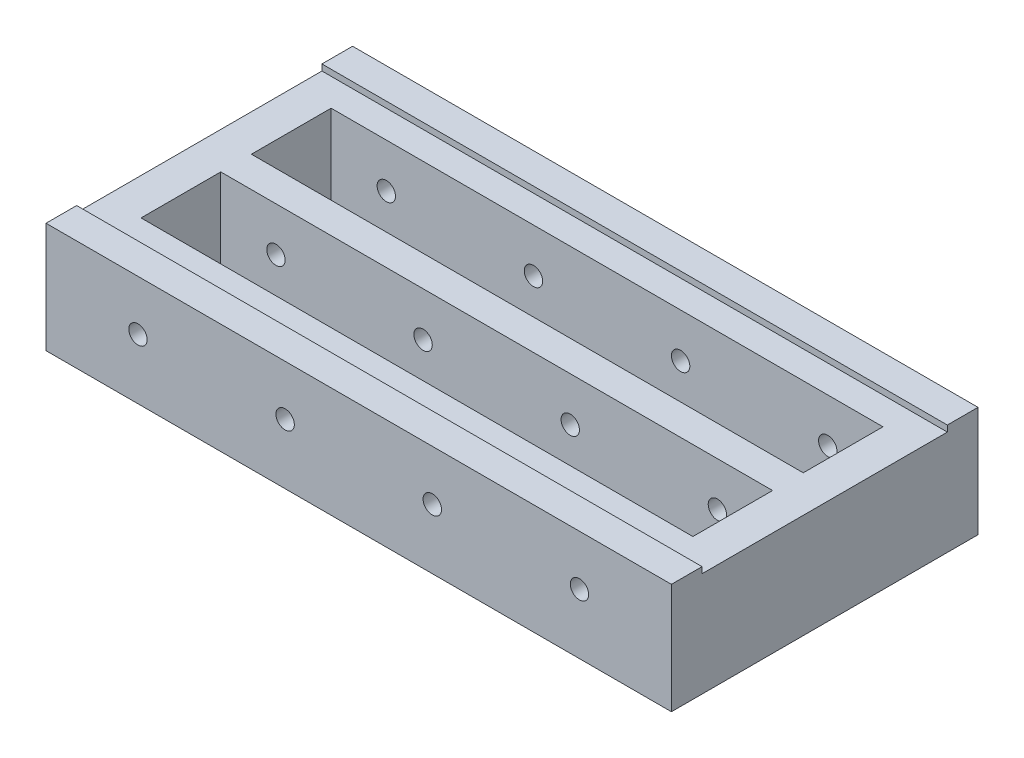
SolidWorks part; units mm, degrees
ref_plane "前视基准面" through (0, 0, 0) normal (0, 0, 1) x (1, 0, 0)
ref_plane "上视基准面" through (0, 0, 0) normal (0, 1, 0) x (1, 0, 0)
ref_plane "右视基准面" through (0, 0, 0) normal (1, 0, 0) x (0, 0, -1)
other "Configuration Table"
sketch "草图1" plane through (0, 0, 0) normal (0, 1, 0) x (1, 0, 0)
  line L0 (-37.5884, 0) -> (30.4411, 0) construction
  line L5 (-25.5, 12.5) -> (25.5, 12.5)
  line L6 (-25.5, 12.5) -> (-25.5, -12.5)
  line L7 (-25.5, -12.5) -> (25.5, -12.5)
  line L8 (25.5, 12.5) -> (25.5, -12.5)
  line L9 (-25.5, 12.5) -> (25.5, -12.5) construction
  line L10 (-25.5, -12.5) -> (25.5, 12.5) construction
  line L11 (-22.5, 7.75) -> (-13.5, 7.75)
  line L12 (-22.5, -1.25) -> (-13.5, -1.25)
  line L13 (-22.5, -1.25) -> (-22.5, -7.75)
  line L14 (-22.5, -7.75) -> (-13.5, -7.75)
  line L15 (-13.5, -1.25) -> (-13.5, -7.75)
  line L20 (-22.5, 7.75) -> (-22.5, 1.25)
  line L21 (-22.5, 1.25) -> (-13.5, 1.25)
  line L22 (-13.5, 7.75) -> (-13.5, 1.25)
  line L23 (-10.5, 7.75) -> (-1.5, 7.75)
  line L24 (-1.5, 7.75) -> (-1.5, 1.25)
  line L25 (-10.5, 1.25) -> (-1.5, 1.25)
  line L26 (-10.5, 7.75) -> (-10.5, 1.25)
  line L27 (-10.5, -1.25) -> (-10.5, -7.75)
  line L28 (-10.5, -1.25) -> (-1.5, -1.25)
  line L29 (-1.5, -1.25) -> (-1.5, -7.75)
  line L30 (-10.5, -7.75) -> (-1.5, -7.75)
  line L31 (1.5, 7.75) -> (10.5, 7.75)
  line L32 (10.5, 7.75) -> (10.5, 1.25)
  line L33 (1.5, 1.25) -> (10.5, 1.25)
  line L34 (1.5, 7.75) -> (1.5, 1.25)
  line L35 (1.5, -1.25) -> (1.5, -7.75)
  line L36 (1.5, -1.25) -> (10.5, -1.25)
  line L37 (10.5, -1.25) -> (10.5, -7.75)
  line L38 (1.5, -7.75) -> (10.5, -7.75)
  line L39 (13.5, 7.75) -> (22.5, 7.75)
  line L40 (22.5, 7.75) -> (22.5, 1.25)
  line L41 (13.5, 1.25) -> (22.5, 1.25)
  line L42 (13.5, 7.75) -> (13.5, 1.25)
  line L43 (13.5, -1.25) -> (13.5, -7.75)
  line L44 (13.5, -1.25) -> (22.5, -1.25)
  line L45 (22.5, -1.25) -> (22.5, -7.75)
  line L46 (13.5, -7.75) -> (22.5, -7.75)
  point P0 (0, 0)
  dimension "D1" = 25
  dimension "D2" = 6.5
  dimension "D3" = 6.5
  dimension "D4" = 3
  dimension "D5" = 51
  dimension "D6" = 9
  dimension "D7" = 1.25
  dimension "D8" = 4
extrude "凸台-拉伸1" add sketch "草图1" along normal blind 9
sketch "草图2" plane through (0, 9, 0) normal (0, 1, 0) x (1, 0, 0)
  line L0 (-25.5, 12.5) -> (-25.5, -12.5) construction
  line L1 (25.5, -10) -> (-25.5, -10)
  line L2 (25.5, -10) -> (25.5, 10)
  line L3 (25.5, 10) -> (-25.5, 10)
  line L4 (-25.5, -10) -> (-25.5, 10)
  line L5 (25.5, -10) -> (-25.5, 10) construction
  line L6 (25.5, 10) -> (-25.5, -10) construction
  line L7 (25.5, 12.5) -> (-25.5, 12.5) construction
  point P0 (0, 0)
  dimension "D1" = 2.5
extrude "切除-拉伸1" cut sketch "草图2" against normal blind 0.5
sketch "草图3" plane through (0, 0, 1.25) normal (0, 0, 1) x (1, 0, 0)
  line L0 (-18, 12.119) -> (-18, -1.4098) construction
  line L1 (-13.5, 8.5) -> (-13.5, 0) construction
  line L2 (-22.5, 8.5) -> (-22.5, 0) construction
  line L3 (-13.5, 8.5) -> (-13.5, 0) construction
  line L4 (-22.5, 8.5) -> (-22.5, 0) construction
  line L6 (25.5, 9) -> (-25.5, 9) construction
  circle A0 centre (-18, 4.9) radius 0.75
  point P8 (0, 0)
  dimension "D2" = 1.5
  dimension "D1" = 4.1
extrude "切除-拉伸2" cut sketch "草图3" against normal through all both and the other way through all contours A0
pattern_linear "阵列(线性)1" count 4 spacing 12 along (1, 0, 0) of "切除-拉伸2"
sketch "草图4" plane through (0, 8.5, 0) normal (0, 1, 0) x (1, 0, 0)
  line L1 (-22.5, 7.75) -> (22.5, 7.75)
  line L2 (-22.5, 7.75) -> (-22.5, 1.25)
  line L3 (-22.5, 1.25) -> (22.5, 1.25)
  line L4 (22.5, 7.75) -> (22.5, 1.25)
  line L5 (22.5, -7.75) -> (-22.5, -7.75)
  line L6 (22.5, -7.75) -> (22.5, -1.25)
  line L7 (22.5, -1.25) -> (-22.5, -1.25)
  line L8 (-22.5, -7.75) -> (-22.5, -1.25)
  point P11 (21.6227, -7.5383)
  point P12 (22.5, -7.75)
extrude "切除-拉伸3" cut sketch "草图4" against normal through all
